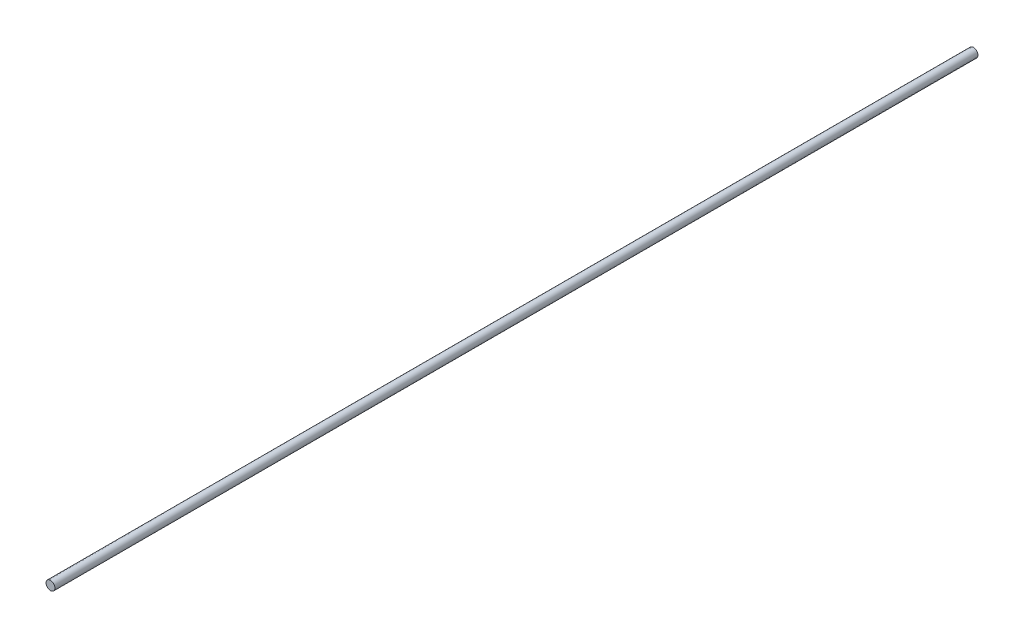
SolidWorks part; units mm, degrees
ref_plane "Alzado" through (0, 0, 0) normal (0, 0, 1) x (1, 0, 0)
ref_plane "Planta" through (0, 0, 0) normal (0, 1, 0) x (1, 0, 0)
ref_plane "Vista lateral" through (0, 0, 0) normal (1, 0, 0) x (0, 0, -1)
sketch "Croquis1" plane through (0, 0, 0) normal (0, 0, 1) x (1, 0, 0)
  circle A0 centre (0, 0) radius 2.95
  dimension "D1" = 5.9
extrude "Saliente-Extruir1" add sketch "Croquis1" against normal blind 609
